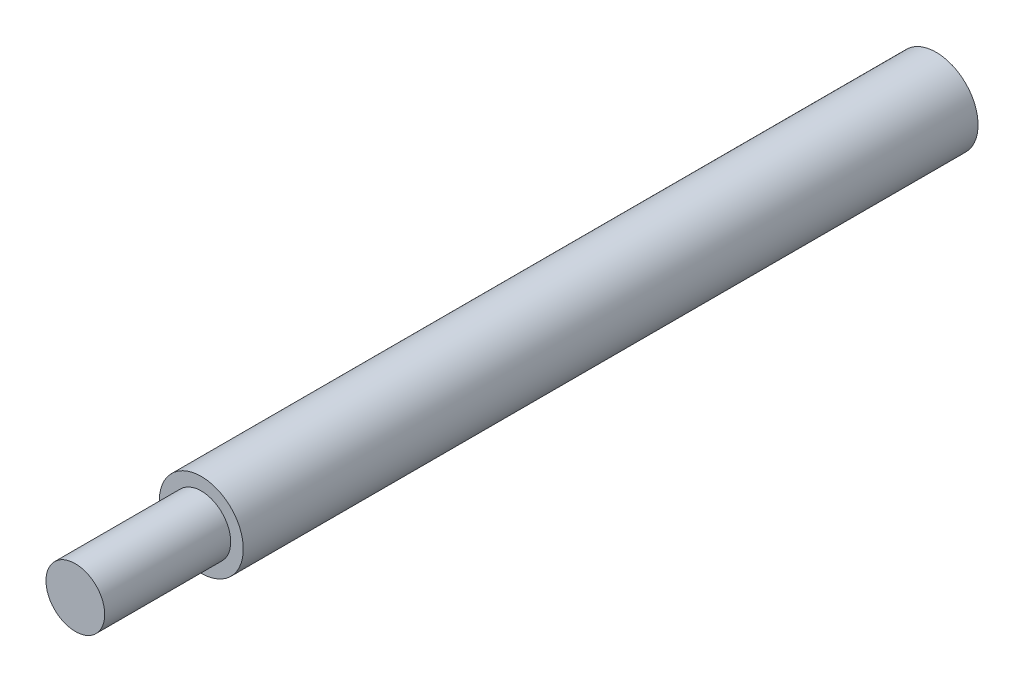
SolidWorks part; units mm, degrees
ref_plane "Front Plane" through (0, 0, 0) normal (0, 0, 1) x (1, 0, 0)
ref_plane "Top Plane" through (0, 0, 0) normal (0, 1, 0) x (1, 0, 0)
ref_plane "Right Plane" through (0, 0, 0) normal (1, 0, 0) x (0, 0, -1)
sketch "Sketch1" plane through (0, 0, 0) normal (0, 0, 1) x (1, 0, 0)
  circle A0 centre (0, 0) radius 1.4
  dimension "D1" = 2.8
extrude "Boss-Extrude1" add sketch "Sketch1" along normal blind 6
sketch "Sketch2" plane through (0, 0, 0) normal (0, 0, -1) x (-1, 0, 0)
  circle A0 centre (0, 0) radius 2
  dimension "D1" = 4
extrude "Boss-Extrude2" add sketch "Sketch2" along normal blind 35
sketch "Sketch3" plane through (0, 0, -35) normal (0, 0, -1) x (-1, 0, 0)
  circle A0 centre (0, 0) radius 1.4
  dimension "D1" = 2.8
extrude "Cut-Extrude1" cut sketch "Sketch3" against normal blind 10
